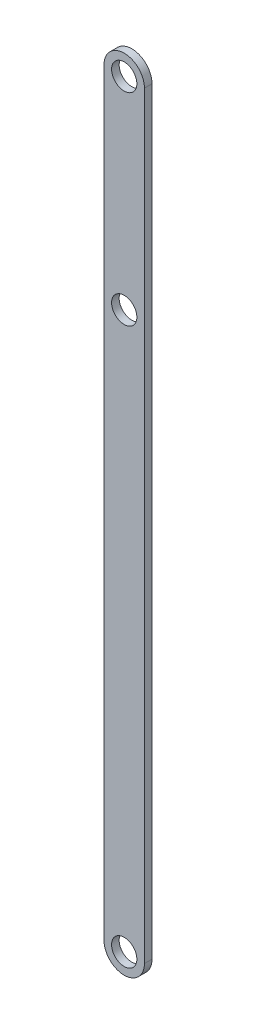
SolidWorks part; units mm, degrees
ref_plane "前基準面" through (0, 0, 0) normal (0, 0, 1) x (1, 0, 0)
ref_plane "上基準面" through (0, 0, 0) normal (0, 1, 0) x (1, 0, 0)
ref_plane "右基準面" through (0, 0, 0) normal (1, 0, 0) x (0, 0, -1)
sketch "草圖1" plane through (0, 0, 0) normal (0, 0, 1) x (1, 0, 0)
  line L0 (0, -15) -> (0, 15) construction
  line L1 (-0.8, -15) -> (-0.8, 15)
  line L2 (0.8, -15) -> (0.8, 15)
  arc A0 (-0.8, -15) -> (0.8, -15) centre (0, -15) ccw
  arc A1 (0.8, 15) -> (-0.8, 15) centre (0, 15) ccw
  circle A2 centre (0, 15) radius 0.5
  circle A3 centre (0, -15) radius 0.5
  circle A4 centre (0, 7) radius 0.5
  point P2 (0, 0)
  dimension "D1" = 1
  dimension "D2" = 0.8
  dimension "D3" = 1
  dimension "D5" = 1
  dimension "D4" = 30
  dimension "D6" = 8
extrude "填料-伸長1" add sketch "草圖1" along normal blind 0.3
